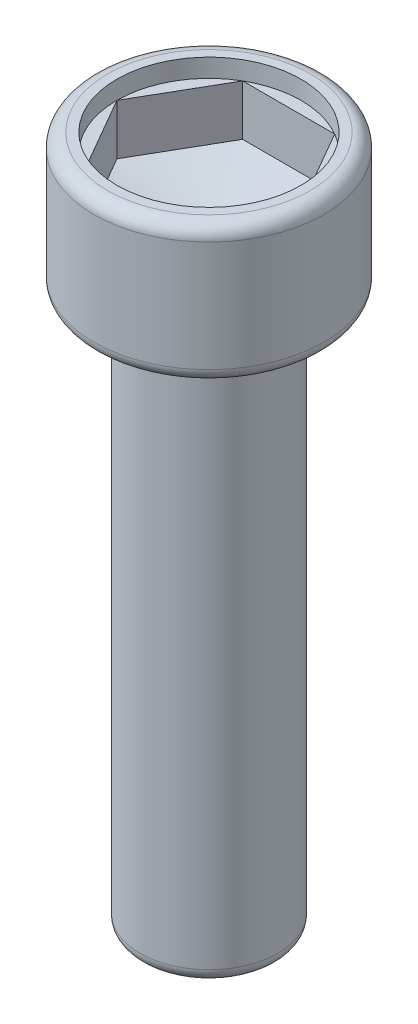
SolidWorks part; units mm, degrees
ref_plane "Front Plane" through (0, 0, 0) normal (0, 0, 1) x (1, 0, 0)
ref_plane "Top Plane" through (0, 0, 0) normal (0, 1, 0) x (1, 0, 0)
ref_plane "Right Plane" through (0, 0, 0) normal (1, 0, 0) x (0, 0, -1)
sketch "Sketch1" plane through (0, 0, 0) normal (0, 1, 0) x (1, 0, 0)
  circle A0 centre (0, 0) radius 2.5
  dimension "D1" = 5
extrude "Boss-Extrude1" add sketch "Sketch1" along normal blind 3
sketch "Sketch2" plane through (0, 3, 0) normal (0, 1, 0) x (1, 0, 0)
  line L1 (2, 0) -> (1, 1.7321)
  line L2 (1, 1.7321) -> (-1, 1.7321)
  line L3 (-1, 1.7321) -> (-2, 0)
  line L4 (-2, 0) -> (-1, -1.7321)
  line L5 (-1, -1.7321) -> (1, -1.7321)
  line L6 (1, -1.7321) -> (2, 0)
  circle A0 centre (0, 0) radius 2 construction
  dimension "D1" = 4
extrude "Cut-Extrude1" cut sketch "Sketch2" against normal blind 1.5
sketch "Sketch5" plane through (0, 1.5, 0) normal (0, 1, 0) x (1, 0, 0)
  circle A0 centre (0, 0) radius 2
extrude "Cut-Extrude2" cut sketch "Sketch5" against normal blind 0.4 from offset 1.5
sketch "Sketch6" plane through (0, 1.5, 0) normal (0, 1, 0) x (1, 0, 0)
  circle A0 centre (0, 0) radius 2
extrude "Cut-Extrude3" cut sketch "Sketch6" against normal blind 0.5 draft 76
sketch "Sketch7" plane through (0, 0, 0) normal (0, -1, 0) x (1, 0, 0)
  circle A0 centre (0, 0) radius 1.5
  dimension "D1" = 3
extrude "Boss-Extrude2" add sketch "Sketch7" along normal blind 12
fillet "Fillet1" radius 0.3 2 edges at (0, 0, 2.5) (0, 3, 2.5)
fillet "Fillet2" radius 0.3 1 edges at (0, -12, -1.5)
